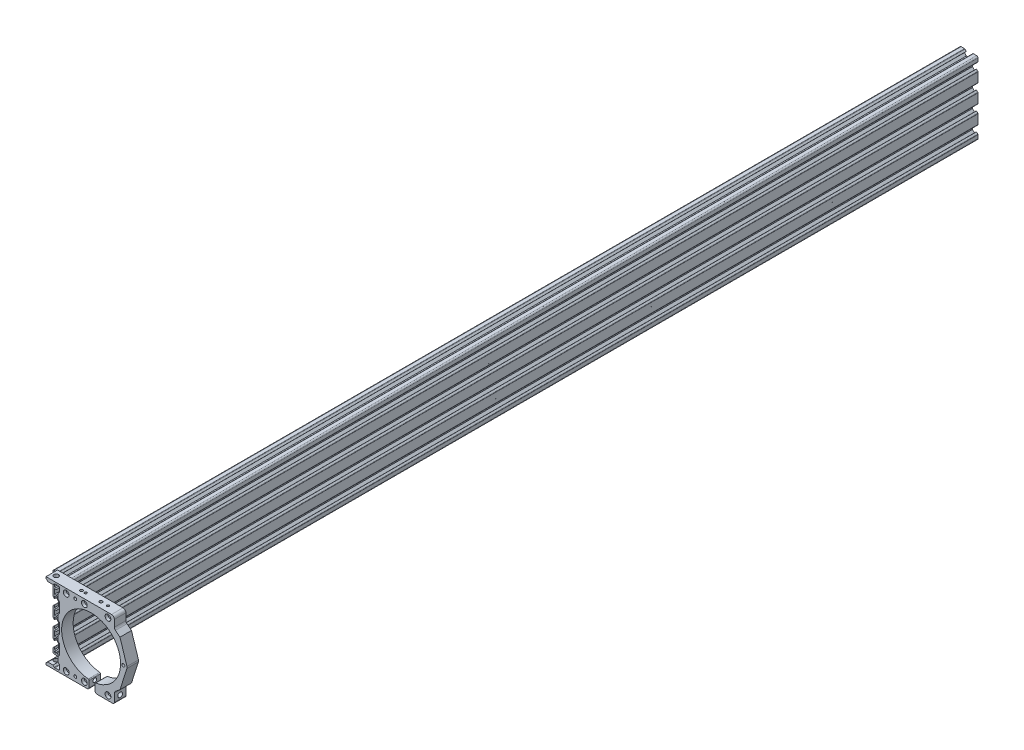
SolidWorks part; units mm, degrees
ref_plane "Front Plane" through (0, 0, 0) normal (0, 0, 1) x (1, 0, 0)
ref_plane "Top Plane" through (0, 0, 0) normal (0, 1, 0) x (1, 0, 0)
ref_plane "Right Plane" through (0, 0, 0) normal (1, 0, 0) x (0, 0, -1)
sketch "Sketch2" plane through (0, 0, 0) normal (0, 0, 1) x (1, 0, 0)
  line L0 (-8.2, 2.8875) -> (-8.2, 5.4975)
  line L3 (-4.9072, 9.9975) -> (-8.5, 9.9975)
  line L4 (-10, 4.9047) -> (-10, 8.4975)
  line L5 (-2.1, 0) -> (-3.8, 0) construction
  line L6 (0, 3.8) -> (0, 2.1) construction
  line L7 (-0.1, 3.9) -> (-2.8404, 3.9)
  line L8 (-3.9, 0.1) -> (-3.9, 2.8383)
  line L9 (-2.89, 8.1975) -> (-5.5, 8.1975)
  line L10 (-6.57, 8.1975) -> (-6.57, 7.6575)
  line L11 (-8.2, 6.5675) -> (-7.66, 6.5675)
  line L12 (-5.5, 8.1975) -> (-5.5, 6.5588)
  line L13 (-6.56, 5.4975) -> (-8.2, 5.4975)
  line L14 (-8.2, 8.1975) -> (-1.4852, 1.4847) construction
  line L15 (-6.56, 5.4975) -> (-3.9, 2.8383)
  line L16 (-5.5, 6.5588) -> (-2.8404, 3.9)
  line L17 (-7.66, 6.5675) -> (-6.57, 7.6575)
  line L18 (-8.7302, 7.6671) -> (-0.5302, -0.5304) construction
  line L19 (-7.6698, 8.7279) -> (0.5302, 0.5304) construction
  line L20 (-8.2, 8.1975) -> (0, 0) construction
  line L21 (-8.2, 6.5675) -> (-8.2, 8.1975)
  line L22 (-8.2, -0.0025) -> (-8.2, 8.1975) construction
  line L23 (-6.57, 8.1975) -> (-8.2, 8.1975)
  line L24 (0, 8.1975) -> (-8.2, 8.1975) construction
  line L25 (-10, -0.0025) -> (-10, 9.9975) construction
  line L26 (0, 9.9975) -> (-10, 9.9975) construction
  line L27 (-2.89, 8.3075) -> (-2.89, 8.1975)
  line L29 (-8.31, 2.8875) -> (-8.2, 2.8875)
  line L30 (-4.3486, 9.7661) -> (-2.89, 8.3075)
  line L31 (-8.31, 2.8875) -> (-9.7686, 4.3461)
  line L34 (-0.1, 3.9) -> (0, 3.8)
  line L35 (-3.9, 0.1) -> (-3.8, 0)
  line L36 (-10, -20) -> (0, -20) construction
  line L37 (0, 0) -> (0, -20) construction
  line L38 (0, -3.9) -> (-2.8404, -3.9)
  line L39 (-3.8, 0) -> (-3.9, -0.1)
  line L40 (-3.9, -0.1) -> (-3.9, -2.84)
  line L41 (-2.8404, -3.9) -> (-6.25, -7.3096)
  line L42 (-3.9, -2.84) -> (-6.56, -5.5)
  line L43 (-8.21, -2.89) -> (-8.21, -5.5)
  line L44 (-6.56, 5.4975) -> (-6.56, -5.5) construction
  line L45 (-6.56, -5.5) -> (-8.21, -5.5)
  line L46 (-6.25, -7.3096) -> (-6.25, -12.7) construction
  line L47 (-6.25, -7.3096) -> (-8.21, -7.3096)
  line L48 (-8.21, -2.89) -> (-8.31, -2.89)
  line L49 (-8.31, -2.89) -> (-9.7657, -4.3457)
  line L51 (-8.21, -7.3096) -> (-8.21, -12.7)
  line L52 (-0.1, -16.1) -> (-2.85, -16.1)
  line L53 (-3.9, -17.16) -> (-3.9, -19.9)
  line L54 (-6.25, -12.7) -> (-2.85, -16.1)
  line L58 (-3.9, -17.16) -> (-6.56, -14.5)
  line L60 (-8.21, -17.11) -> (-8.31, -17.11)
  line L61 (-10, -4.9114) -> (-10, -15.0886)
  line L62 (-9.7657, -15.6543) -> (-8.31, -17.11)
  line L63 (-0.1, -16.1) -> (0, -16.2)
  line L64 (-3.9, -19.9) -> (-3.8, -20)
  line L65 (-8.21, -14.5) -> (-6.56, -14.5)
  line L66 (-8.21, -12.7) -> (-6.25, -12.7)
  line L67 (-10, -30.01) -> (0, -30.01) construction
  line L68 (-8.21, -14.5) -> (-8.21, -17.11)
  line L69 (-3.9, -20.1) -> (-3.8, -20)
  line L71 (-10, -20) -> (0, -20) construction
  line L72 (-8.21, -30.01) -> (-8.21, -27.31)
  line L73 (-10, -30.01) -> (-10, -24.9101)
  line L74 (-8.21, -25.4987) -> (-8.21, -22.8887)
  line L76 (-8.21, -27.31) -> (-6.25, -27.31)
  line L77 (-8.21, -25.4987) -> (-6.56, -25.4987)
  line L85 (-0.1, -23.9) -> (0, -23.8)
  line L95 (-9.7657, -24.3444) -> (-8.31, -22.8887)
  line L96 (-8.21, -22.8887) -> (-8.31, -22.8887)
  line L97 (-3.9, -22.8387) -> (-6.56, -25.4987)
  line L98 (-6.25, -27.31) -> (-2.84, -23.9)
  line L99 (-3.9, -22.8387) -> (-3.9, -20.1)
  line L100 (-0.1, -23.9) -> (-2.84, -23.9)
  arc A1 (-10, 8.4975) -> (-8.5, 9.9975) centre (-8.5, 8.4975) cw
  arc A2 (-9.7686, 4.3461) -> (-10, 4.9047) centre (-9.21, 4.9047) cw
  arc A3 (-4.3486, 9.7661) -> (-4.9072, 9.9975) centre (-4.9072, 9.2075) ccw
  arc A5 (0, 2.1) -> (0, -2.1) centre (0, 0) ccw
  arc A6 (-9.7657, -15.6543) -> (-10, -15.0886) centre (-9.2, -15.0886) cw
  arc A7 (-9.7657, -4.3457) -> (-10, -4.9114) centre (-9.2, -4.9114) ccw
  arc A8 (0, -17.9) -> (0, -22.1) centre (0, -20) ccw
  arc A10 (-9.7657, -24.3444) -> (-10, -24.9101) centre (-9.2, -24.9101) ccw
  point P29 (-10, 9.9975)
  point P39 (-10, 4.5775)
  point P42 (-4.58, 9.9975)
  point P76 (-10, -15.42)
  point P79 (-10, -4.58)
  dimension "D15" = 1.5
  dimension "D22" = 0.79
  dimension "D30" = 2.1
  dimension "D31" = 2.1
  dimension "D51" = 0.8
  dimension "D52" = 2.61
  dimension "D64" = 1.65
  dimension "D53" = 0.8
  dimension "D55" = 3.9
  dimension "D4" = 1.8
  dimension "D5" = 3.43
  dimension "D6" = 3.43
  dimension "D7" = 0.54
  dimension "D8" = 0.54
  dimension "D9" = 1.07
  dimension "D10" = 1.07
  dimension "D11" = 3.9
  dimension "D12" = 3.9
  dimension "D16" = 7.11
  dimension "D17" = 0.11
  dimension "D18" = 1.69
  dimension "D19" = 0.11
  dimension "D20" = 7.11
  dimension "D21" = 1.69
  dimension "D23" = 10
  dimension "D24" = 0.1
  dimension "D25" = 45
  dimension "D26" = 0.1
  dimension "D27" = 45
  dimension "D28" = 1.64
  dimension "D29" = 20
  dimension "D32" = 3.9
  dimension "D33" = 45
  dimension "D34" = 2.74
  dimension "D35" = 45
  dimension "D36" = 1.96
  dimension "D37" = 2.61
  dimension "D38" = 90
  dimension "D39" = 2.61
  dimension "D40" = 3.9
  dimension "D41" = 3.9
  dimension "D42" = 135
  dimension "D44" = 45
  dimension "D45" = 1.8
  dimension "D46" = 0.1
  dimension "D47" = 0.1
  dimension "D48" = 45
  dimension "D49" = 0.1
  dimension "D50" = 45
  dimension "D43" = 5.5
  dimension "D54" = 3.9
  dimension "D56" = 45
  dimension "D57" = 2.7
  dimension "D59" = 45
  dimension "D60" = 0.1
  dimension "D61" = 0.1
  dimension "D62" = 45
  dimension "D63" = 2.84
  dimension "D65" = 1.96
  dimension "D66" = 45
  dimension "D67" = 1.5
  dimension "D13" = 0.75
  dimension "D14" = 0.75
sketch "Sketch3" plane through (0, 0, 0) normal (0, 0, 1) x (1, 0, 0)
  line L0 (-0.1, 3.9) -> (0, 3.8) construction
  line L1 (-0.1, 3.9) -> (-2.8404, 3.9) construction
  line L2 (-5.5, 6.5588) -> (-2.8404, 3.9) construction
  line L3 (-5.5, 8.1975) -> (-5.5, 6.5588) construction
  line L4 (-2.89, 8.1975) -> (-5.5, 8.1975) construction
  line L5 (-7.66, 6.5675) -> (-6.57, 7.6575)
  line L6 (-6.57, 7.6575) -> (-6.57, 8.1975)
  line L7 (-6.57, 8.1975) -> (-8.2, 8.1975)
  line L8 (-8.2, 8.1975) -> (-8.2, 6.5675)
  line L9 (-8.2, 6.5675) -> (-7.66, 6.5675)
  line L10 (-7.66, 6.5675) -> (-6.57, 7.6575)
  line L11 (-6.57, 7.6575) -> (-6.57, 8.1975)
  line L12 (-6.57, 8.1975) -> (-8.2, 8.1975)
  line L13 (-8.2, 8.1975) -> (-8.2, 6.5675)
  line L14 (-8.2, 6.5675) -> (-7.66, 6.5675)
  line L15 (-2.89, 8.3075) -> (-2.89, 8.1975) construction
  line L16 (-4.3486, 9.7661) -> (-2.89, 8.3075) construction
  line L17 (-4.9072, 9.9975) -> (-8.5, 9.9975) construction
  line L18 (-10, 4.9047) -> (-10, 8.4975) construction
  line L19 (-8.31, 2.8875) -> (-9.7686, 4.3461) construction
  line L20 (-8.31, 2.8875) -> (-8.2, 2.8875) construction
  line L21 (-8.2, 2.8875) -> (-8.2, 5.4975) construction
  line L22 (-6.56, 5.4975) -> (-8.2, 5.4975) construction
  line L23 (-6.56, 5.4975) -> (-3.9, 2.8383) construction
  line L24 (-3.9, 0.1) -> (-3.9, 2.8383) construction
  line L25 (-3.9, 0.1) -> (-3.8, 0) construction
  line L26 (-3.8, 0) -> (-3.9, -0.1) construction
  line L27 (-3.9, -0.1) -> (-3.9, -2.84) construction
  line L28 (-3.9, -2.84) -> (-6.56, -5.5) construction
  line L29 (-6.56, -5.5) -> (-8.21, -5.5) construction
  line L30 (-8.21, -2.89) -> (-8.21, -5.5) construction
  line L31 (-8.21, -2.89) -> (-8.31, -2.89) construction
  line L32 (-8.31, -2.89) -> (-9.7657, -4.3457) construction
  line L33 (-10, -4.9114) -> (-10, -15.0886) construction
  line L34 (-9.7657, -15.6543) -> (-8.31, -17.11) construction
  line L35 (-8.21, -17.11) -> (-8.31, -17.11) construction
  line L36 (-8.21, -14.5) -> (-8.21, -17.11) construction
  line L37 (-8.21, -14.5) -> (-6.56, -14.5) construction
  line L38 (-3.9, -17.16) -> (-6.56, -14.5) construction
  line L39 (-3.9, -17.16) -> (-3.9, -19.9) construction
  line L40 (-3.9, -19.9) -> (-3.8, -20) construction
  line L41 (-3.9, -20.1) -> (-3.8, -20) construction
  line L42 (-3.9, -22.8387) -> (-3.9, -20.1) construction
  line L43 (-3.9, -22.8387) -> (-6.56, -25.4987) construction
  line L44 (-8.21, -25.4987) -> (-6.56, -25.4987) construction
  line L45 (-8.21, -25.4987) -> (-8.21, -22.8887) construction
  line L46 (-8.21, -22.8887) -> (-8.31, -22.8887) construction
  line L47 (-9.7657, -24.3444) -> (-8.31, -22.8887) construction
  line L48 (-10, -30.01) -> (-10, -24.9101) construction
  line L49 (0, -3.9) -> (-2.8404, -3.9) construction
  line L50 (-2.8404, -3.9) -> (-6.25, -7.3096) construction
  line L51 (-6.25, -7.3096) -> (-8.21, -7.3096) construction
  line L52 (-8.21, -7.3096) -> (-8.21, -12.7) construction
  line L53 (-8.21, -12.7) -> (-6.25, -12.7) construction
  line L54 (-6.25, -12.7) -> (-2.85, -16.1) construction
  line L55 (-0.1, -16.1) -> (-2.85, -16.1) construction
  line L56 (-0.1, -16.1) -> (0, -16.2) construction
  line L57 (-0.1, -23.9) -> (0, -23.8) construction
  line L58 (-0.1, -23.9) -> (-2.84, -23.9) construction
  line L59 (-6.25, -27.31) -> (-2.84, -23.9) construction
  line L60 (-8.21, -27.31) -> (-6.25, -27.31) construction
  line L61 (-8.21, -30.01) -> (-8.21, -27.31) construction
  line L62 (-0.1, 3.9) -> (0, 3.8)
  line L63 (-0.1, 3.9) -> (-2.8404, 3.9)
  line L64 (-5.5, 6.5588) -> (-2.8404, 3.9)
  line L65 (-5.5, 8.1975) -> (-5.5, 6.5588)
  line L66 (-2.89, 8.1975) -> (-5.5, 8.1975)
  line L67 (-2.89, 8.3075) -> (-2.89, 8.1975)
  line L68 (-4.3486, 9.7661) -> (-2.89, 8.3075)
  line L69 (-4.9072, 9.9975) -> (-8.5, 9.9975)
  line L70 (-10, 4.9047) -> (-10, 8.4975)
  line L71 (-8.31, 2.8875) -> (-9.7686, 4.3461)
  line L72 (-8.31, 2.8875) -> (-8.2, 2.8875)
  line L73 (-8.2, 2.8875) -> (-8.2, 5.4975)
  line L74 (-6.56, 5.4975) -> (-8.2, 5.4975)
  line L75 (-6.56, 5.4975) -> (-3.9, 2.8383)
  line L76 (-3.9, 0.1) -> (-3.9, 2.8383)
  line L77 (-3.9, 0.1) -> (-3.8, 0)
  line L78 (-3.8, 0) -> (-3.9, -0.1)
  line L79 (-3.9, -0.1) -> (-3.9, -2.84)
  line L80 (-3.9, -2.84) -> (-6.56, -5.5)
  line L81 (-6.56, -5.5) -> (-8.21, -5.5)
  line L82 (-8.21, -2.89) -> (-8.21, -5.5)
  line L83 (-8.21, -2.89) -> (-8.31, -2.89)
  line L84 (-8.31, -2.89) -> (-9.7657, -4.3457)
  line L85 (-10, -4.9114) -> (-10, -15.0886)
  line L86 (-9.7657, -15.6543) -> (-8.31, -17.11)
  line L87 (-8.21, -17.11) -> (-8.31, -17.11)
  line L88 (-8.21, -14.5) -> (-8.21, -17.11)
  line L89 (-8.21, -14.5) -> (-6.56, -14.5)
  line L90 (-3.9, -17.16) -> (-6.56, -14.5)
  line L91 (-3.9, -17.16) -> (-3.9, -19.9)
  line L92 (-3.9, -19.9) -> (-3.8, -20)
  line L93 (-3.9, -20.1) -> (-3.8, -20)
  line L94 (-3.9, -22.8387) -> (-3.9, -20.1)
  line L95 (-3.9, -22.8387) -> (-6.56, -25.4987)
  line L96 (-8.21, -25.4987) -> (-6.56, -25.4987)
  line L97 (-8.21, -25.4987) -> (-8.21, -22.8887)
  line L98 (-8.21, -22.8887) -> (-8.31, -22.8887)
  line L99 (-9.7657, -24.3444) -> (-8.31, -22.8887)
  line L100 (-10, -35.1099) -> (-10, -24.9101)
  line L101 (2.8404, -3.9) -> (-2.8404, -3.9)
  line L102 (-2.8404, -3.9) -> (-6.25, -7.3096)
  line L103 (-6.25, -7.3096) -> (-8.21, -7.3096)
  line L104 (-8.21, -7.3096) -> (-8.21, -12.7)
  line L105 (-8.21, -12.7) -> (-6.25, -12.7)
  line L106 (-6.25, -12.7) -> (-2.85, -16.1)
  line L107 (-0.1, -16.1) -> (-2.85, -16.1)
  line L108 (-0.1, -16.1) -> (0, -16.2)
  line L109 (-0.1, -23.9) -> (0, -23.8)
  line L110 (-0.1, -23.9) -> (-2.84, -23.9)
  line L111 (-6.25, -27.31) -> (-2.84, -23.9)
  line L112 (-8.21, -27.31) -> (-6.25, -27.31)
  line L113 (-8.21, -32.71) -> (-8.21, -27.31)
  line L114 (0, 0) -> (0, -20) construction
  line L115 (-10, -30.01) -> (0, -30.01) construction
  line L116 (0, 0) -> (0, -20) construction
  line L117 (-10, -30.01) -> (10, -30.01) construction
  line L118 (8.21, -32.71) -> (8.21, -27.31)
  line L119 (8.21, -27.31) -> (6.25, -27.31)
  line L120 (6.25, -27.31) -> (2.84, -23.9)
  line L121 (0.1, -23.9) -> (2.84, -23.9)
  line L122 (0.1, -23.9) -> (0, -23.8)
  line L123 (0.1, -16.1) -> (0, -16.2)
  line L124 (0.1, -16.1) -> (2.85, -16.1)
  line L125 (6.25, -12.7) -> (2.85, -16.1)
  line L126 (8.21, -12.7) -> (6.25, -12.7)
  line L127 (8.21, -7.3096) -> (8.21, -12.7)
  line L128 (6.25, -7.3096) -> (8.21, -7.3096)
  line L129 (2.8404, -3.9) -> (6.25, -7.3096)
  line L130 (10, -35.1099) -> (10, -24.9101)
  line L131 (9.7657, -24.3444) -> (8.31, -22.8887)
  line L132 (8.21, -22.8887) -> (8.31, -22.8887)
  line L133 (8.21, -25.4987) -> (8.21, -22.8887)
  line L134 (8.21, -25.4987) -> (6.56, -25.4987)
  line L135 (3.9, -22.8387) -> (6.56, -25.4987)
  line L136 (3.9, -22.8387) -> (3.9, -20.1)
  line L137 (3.9, -20.1) -> (3.8, -20)
  line L138 (3.9, -19.9) -> (3.8, -20)
  line L139 (3.9, -17.16) -> (3.9, -19.9)
  line L140 (3.9, -17.16) -> (6.56, -14.5)
  line L141 (8.21, -14.5) -> (6.56, -14.5)
  line L142 (8.21, -14.5) -> (8.21, -17.11)
  line L143 (8.21, -17.11) -> (8.31, -17.11)
  line L144 (9.7657, -15.6543) -> (8.31, -17.11)
  line L145 (10, -4.9114) -> (10, -15.0886)
  line L146 (8.31, -2.89) -> (9.7657, -4.3457)
  line L147 (8.21, -2.89) -> (8.31, -2.89)
  line L148 (8.21, -2.89) -> (8.21, -5.5)
  line L149 (6.56, -5.5) -> (8.21, -5.5)
  line L150 (3.9, -2.84) -> (6.56, -5.5)
  line L151 (3.9, -0.1) -> (3.9, -2.84)
  line L152 (3.8, 0) -> (3.9, -0.1)
  line L153 (3.9, 0.1) -> (3.8, 0)
  line L154 (3.9, 0.1) -> (3.9, 2.8383)
  line L155 (6.56, 5.4975) -> (3.9, 2.8383)
  line L156 (6.56, 5.4975) -> (8.2, 5.4975)
  line L157 (8.2, 2.8875) -> (8.2, 5.4975)
  line L158 (8.31, 2.8875) -> (8.2, 2.8875)
  line L159 (8.31, 2.8875) -> (9.7686, 4.3461)
  line L160 (10, 4.9047) -> (10, 8.4975)
  line L161 (4.9072, 9.9975) -> (8.5, 9.9975)
  line L162 (4.3486, 9.7661) -> (2.89, 8.3075)
  line L163 (2.89, 8.3075) -> (2.89, 8.1975)
  line L164 (2.89, 8.1975) -> (5.5, 8.1975)
  line L165 (5.5, 8.1975) -> (5.5, 6.5588)
  line L166 (5.5, 6.5588) -> (2.8404, 3.9)
  line L167 (0.1, 3.9) -> (2.8404, 3.9)
  line L168 (0.1, 3.9) -> (0, 3.8)
  line L169 (8.2, 6.5675) -> (7.66, 6.5675)
  line L170 (8.2, 8.1975) -> (8.2, 6.5675)
  line L171 (6.57, 8.1975) -> (8.2, 8.1975)
  line L172 (6.57, 7.6575) -> (6.57, 8.1975)
  line L173 (7.66, 6.5675) -> (6.57, 7.6575)
  line L174 (0, -60.02) -> (0, -40.02) construction
  line L175 (7.66, -66.5875) -> (6.57, -67.6775)
  line L176 (6.57, -67.6775) -> (6.57, -68.2175)
  line L177 (6.57, -68.2175) -> (8.2, -68.2175)
  line L178 (8.2, -68.2175) -> (8.2, -66.5875)
  line L179 (8.2, -66.5875) -> (7.66, -66.5875)
  line L180 (0.1, -63.92) -> (0, -63.82)
  line L181 (0.1, -63.92) -> (2.8404, -63.92)
  line L182 (5.5, -66.5788) -> (2.8404, -63.92)
  line L183 (5.5, -68.2175) -> (5.5, -66.5788)
  line L184 (2.89, -68.2175) -> (5.5, -68.2175)
  line L185 (2.89, -68.3275) -> (2.89, -68.2175)
  line L186 (4.3486, -69.7861) -> (2.89, -68.3275)
  line L187 (4.9072, -70.0175) -> (8.5, -70.0175)
  line L188 (10, -64.9247) -> (10, -68.5175)
  line L189 (8.31, -62.9075) -> (9.7686, -64.3661)
  line L190 (8.31, -62.9075) -> (8.2, -62.9075)
  line L191 (8.2, -62.9075) -> (8.2, -65.5175)
  line L192 (6.56, -65.5175) -> (8.2, -65.5175)
  line L193 (6.56, -65.5175) -> (3.9, -62.8583)
  line L194 (3.9, -60.12) -> (3.9, -62.8583)
  line L195 (3.9, -60.12) -> (3.8, -60.02)
  line L196 (3.8, -60.02) -> (3.9, -59.92)
  line L197 (3.9, -59.92) -> (3.9, -57.18)
  line L198 (3.9, -57.18) -> (6.56, -54.52)
  line L199 (6.56, -54.52) -> (8.21, -54.52)
  line L200 (8.21, -57.13) -> (8.21, -54.52)
  line L201 (8.21, -57.13) -> (8.31, -57.13)
  line L202 (8.31, -57.13) -> (9.7657, -55.6743)
  line L203 (10, -55.1086) -> (10, -44.9314)
  line L204 (9.7657, -44.3657) -> (8.31, -42.91)
  line L205 (8.21, -42.91) -> (8.31, -42.91)
  line L206 (8.21, -45.52) -> (8.21, -42.91)
  line L207 (8.21, -45.52) -> (6.56, -45.52)
  line L208 (3.9, -42.86) -> (6.56, -45.52)
  line L209 (3.9, -42.86) -> (3.9, -40.12)
  line L210 (3.9, -40.12) -> (3.8, -40.02)
  line L211 (3.9, -39.92) -> (3.8, -40.02)
  line L212 (3.9, -37.1813) -> (3.9, -39.92)
  line L213 (3.9, -37.1813) -> (6.56, -34.5213)
  line L214 (8.21, -34.5213) -> (6.56, -34.5213)
  line L215 (8.21, -34.5213) -> (8.21, -37.1313)
  line L216 (8.21, -37.1313) -> (8.31, -37.1313)
  line L217 (9.7657, -35.6756) -> (8.31, -37.1313)
  line L218 (2.8404, -56.12) -> (6.25, -52.7104)
  line L219 (6.25, -52.7104) -> (8.21, -52.7104)
  line L220 (8.21, -52.7104) -> (8.21, -47.32)
  line L221 (8.21, -47.32) -> (6.25, -47.32)
  line L222 (6.25, -47.32) -> (2.85, -43.92)
  line L223 (0.1, -43.92) -> (2.85, -43.92)
  line L224 (0.1, -43.92) -> (0, -43.82)
  line L225 (0.1, -36.12) -> (0, -36.22)
  line L226 (0.1, -36.12) -> (2.84, -36.12)
  line L227 (6.25, -32.71) -> (2.84, -36.12)
  line L228 (8.21, -32.71) -> (6.25, -32.71)
  line L229 (-8.21, -32.71) -> (-6.25, -32.71)
  line L230 (-6.25, -32.71) -> (-2.84, -36.12)
  line L231 (-0.1, -36.12) -> (-2.84, -36.12)
  line L232 (-0.1, -36.12) -> (0, -36.22)
  line L233 (-0.1, -43.92) -> (0, -43.82)
  line L234 (-0.1, -43.92) -> (-2.85, -43.92)
  line L235 (-6.25, -47.32) -> (-2.85, -43.92)
  line L236 (-8.21, -47.32) -> (-6.25, -47.32)
  line L237 (-8.21, -52.7104) -> (-8.21, -47.32)
  line L238 (-6.25, -52.7104) -> (-8.21, -52.7104)
  line L239 (-2.8404, -56.12) -> (-6.25, -52.7104)
  line L240 (2.8404, -56.12) -> (-2.8404, -56.12)
  line L241 (-9.7657, -35.6756) -> (-8.31, -37.1313)
  line L242 (-8.21, -37.1313) -> (-8.31, -37.1313)
  line L243 (-8.21, -34.5213) -> (-8.21, -37.1313)
  line L244 (-8.21, -34.5213) -> (-6.56, -34.5213)
  line L245 (-3.9, -37.1813) -> (-6.56, -34.5213)
  line L246 (-3.9, -37.1813) -> (-3.9, -39.92)
  line L247 (-3.9, -39.92) -> (-3.8, -40.02)
  line L248 (-3.9, -40.12) -> (-3.8, -40.02)
  line L249 (-3.9, -42.86) -> (-3.9, -40.12)
  line L250 (-3.9, -42.86) -> (-6.56, -45.52)
  line L251 (-8.21, -45.52) -> (-6.56, -45.52)
  line L252 (-8.21, -45.52) -> (-8.21, -42.91)
  line L253 (-8.21, -42.91) -> (-8.31, -42.91)
  line L254 (-9.7657, -44.3657) -> (-8.31, -42.91)
  line L255 (-10, -55.1086) -> (-10, -44.9314)
  line L256 (-8.31, -57.13) -> (-9.7657, -55.6743)
  line L257 (-8.21, -57.13) -> (-8.31, -57.13)
  line L258 (-8.21, -57.13) -> (-8.21, -54.52)
  line L259 (-6.56, -54.52) -> (-8.21, -54.52)
  line L260 (-3.9, -57.18) -> (-6.56, -54.52)
  line L261 (-3.9, -59.92) -> (-3.9, -57.18)
  line L262 (-3.8, -60.02) -> (-3.9, -59.92)
  line L263 (-3.9, -60.12) -> (-3.8, -60.02)
  line L264 (-3.9, -60.12) -> (-3.9, -62.8583)
  line L265 (-6.56, -65.5175) -> (-3.9, -62.8583)
  line L266 (-6.56, -65.5175) -> (-8.2, -65.5175)
  line L267 (-8.2, -62.9075) -> (-8.2, -65.5175)
  line L268 (-8.31, -62.9075) -> (-8.2, -62.9075)
  line L269 (-8.31, -62.9075) -> (-9.7686, -64.3661)
  line L270 (-10, -64.9247) -> (-10, -68.5175)
  line L271 (-4.9072, -70.0175) -> (-8.5, -70.0175)
  line L272 (-4.3486, -69.7861) -> (-2.89, -68.3275)
  line L273 (-2.89, -68.3275) -> (-2.89, -68.2175)
  line L274 (-2.89, -68.2175) -> (-5.5, -68.2175)
  line L275 (-5.5, -68.2175) -> (-5.5, -66.5788)
  line L276 (-5.5, -66.5788) -> (-2.8404, -63.92)
  line L277 (-0.1, -63.92) -> (-2.8404, -63.92)
  line L278 (-0.1, -63.92) -> (0, -63.82)
  line L279 (-8.2, -66.5875) -> (-7.66, -66.5875)
  line L280 (-8.2, -68.2175) -> (-8.2, -66.5875)
  line L281 (-6.57, -68.2175) -> (-8.2, -68.2175)
  line L282 (-6.57, -67.6775) -> (-6.57, -68.2175)
  line L283 (-7.66, -66.5875) -> (-6.57, -67.6775)
  arc A0 (0, 2.1) -> (0, -2.1) centre (0, 0) ccw construction
  arc A1 (0, -17.9) -> (0, -22.1) centre (0, -20) ccw construction
  arc A2 (-4.3486, 9.7661) -> (-4.9072, 9.9975) centre (-4.9072, 9.2075) ccw construction
  arc A3 (-8.5, 9.9975) -> (-10, 8.4975) centre (-8.5, 8.4975) ccw construction
  arc A4 (-10, 4.9047) -> (-9.7686, 4.3461) centre (-9.21, 4.9047) ccw construction
  arc A5 (-9.7657, -4.3457) -> (-10, -4.9114) centre (-9.2, -4.9114) ccw construction
  arc A6 (-10, -15.0886) -> (-9.7657, -15.6543) centre (-9.2, -15.0886) ccw construction
  arc A7 (-9.7657, -24.3444) -> (-10, -24.9101) centre (-9.2, -24.9101) ccw construction
  circle A8 centre (0, 0) radius 2.1
  circle A9 centre (0, -20) radius 2.1
  arc A10 (-4.3486, 9.7661) -> (-4.9072, 9.9975) centre (-4.9072, 9.2075) ccw
  arc A11 (-8.5, 9.9975) -> (-10, 8.4975) centre (-8.5, 8.4975) ccw
  arc A12 (-10, 4.9047) -> (-9.7686, 4.3461) centre (-9.21, 4.9047) ccw
  arc A13 (-9.7657, -4.3457) -> (-10, -4.9114) centre (-9.2, -4.9114) ccw
  arc A14 (-10, -15.0886) -> (-9.7657, -15.6543) centre (-9.2, -15.0886) ccw
  arc A15 (-9.7657, -24.3444) -> (-10, -24.9101) centre (-9.2, -24.9101) ccw
  arc A16 (9.7657, -24.3444) -> (10, -24.9101) centre (9.2, -24.9101) cw
  arc A17 (10, -15.0886) -> (9.7657, -15.6543) centre (9.2, -15.0886) cw
  arc A18 (9.7657, -4.3457) -> (10, -4.9114) centre (9.2, -4.9114) cw
  arc A19 (10, 4.9047) -> (9.7686, 4.3461) centre (9.21, 4.9047) cw
  arc A20 (8.5, 9.9975) -> (10, 8.4975) centre (8.5, 8.4975) cw
  arc A21 (4.3486, 9.7661) -> (4.9072, 9.9975) centre (4.9072, 9.2075) cw
  arc A22 (4.3486, -69.7861) -> (4.9072, -70.0175) centre (4.9072, -69.2275) ccw
  arc A23 (8.5, -70.0175) -> (10, -68.5175) centre (8.5, -68.5175) ccw
  arc A24 (10, -64.9247) -> (9.7686, -64.3661) centre (9.21, -64.9247) ccw
  arc A25 (9.7657, -55.6743) -> (10, -55.1086) centre (9.2, -55.1086) ccw
  arc A26 (10, -44.9314) -> (9.7657, -44.3657) centre (9.2, -44.9314) ccw
  arc A27 (9.7657, -35.6756) -> (10, -35.1099) centre (9.2, -35.1099) ccw
  arc A28 (-9.7657, -35.6756) -> (-10, -35.1099) centre (-9.2, -35.1099) cw
  arc A29 (-10, -44.9314) -> (-9.7657, -44.3657) centre (-9.2, -44.9314) cw
  arc A30 (-9.7657, -55.6743) -> (-10, -55.1086) centre (-9.2, -55.1086) cw
  arc A31 (-10, -64.9247) -> (-9.7686, -64.3661) centre (-9.21, -64.9247) cw
  arc A32 (-8.5, -70.0175) -> (-10, -68.5175) centre (-8.5, -68.5175) cw
  arc A33 (-4.3486, -69.7861) -> (-4.9072, -70.0175) centre (-4.9072, -69.2275) cw
  circle A34 centre (0, -40.02) radius 2.1
  circle A35 centre (0, -60.02) radius 2.1
  point P240 (8.21, -30.01)
  point P288 (-0.1, 9.9975)
  point P289 (0, -70.0175)
  point P290 (-10, -60.02)
  point P291 (10, -60.02)
  point P292 (10, -40.02)
  point P293 (-10, -40.02)
  point P294 (-10, -20)
  point P295 (10, -20)
  point P296 (10, 0)
  point P297 (-10, 0)
  point P298 (-45.6583, 8.4975)
  dimension "D1" = 0
extrude "Boss-Extrude1" add sketch "Sketch3" against normal blind 1000
sketch "Sketch7" plane through (0, 0, 0) normal (0, 0, 1) x (1, 0, 0)
  line L0 (-10, -24.9101) -> (-10, -35.1099) construction
  line L1 (-8.2, -68.2175) -> (-6.57, -68.2175) construction
  line L2 (10.1, 12.0975) -> (67.3634, 12.0975)
  line L3 (70.4884, -70.1175) -> (70.4884, -61.5188)
  line L4 (8.3807, 2.8168) -> (9.8393, 4.2754)
  line L5 (10.1, 4.9047) -> (10.1, 8.4975)
  line L6 (8.3807, 2.8168) -> (9.8393, 4.2754)
  line L7 (10.1, 4.9047) -> (10.1, 8.4975)
  line L8 (49.1638, -63.0778) -> (49.1638, -70.1175)
  line L9 (70.4884, 1.4988) -> (70.4884, 8.9725)
  line L10 (51.1638, -72.1175) -> (68.4884, -72.1175)
  line L11 (42.5638, -63.3533) -> (42.5638, -70.1175)
  line L12 (8.3807, -17.1807) -> (9.8364, -15.725)
  line L13 (10.1, -15.0886) -> (10.1, -4.9114)
  line L14 (9.8364, -4.275) -> (8.3807, -2.8193)
  line L15 (8.3807, -17.1807) -> (9.8364, -15.725)
  line L16 (10.1, -15.0886) -> (10.1, -4.9114)
  line L17 (9.8364, -4.275) -> (8.3807, -2.8193)
  line L18 (40.5638, -72.1175) -> (10.1, -72.1175)
  line L34 (8.3807, -37.202) -> (9.8364, -35.7463)
  line L35 (10.1, -35.1099) -> (10.1, -24.9101)
  line L36 (9.8364, -24.2737) -> (8.3807, -22.818)
  line L37 (8.3807, -37.202) -> (9.8364, -35.7463)
  line L38 (10.1, -35.1099) -> (10.1, -24.9101)
  line L39 (9.8364, -24.2737) -> (8.3807, -22.818)
  line L43 (8.3807, -57.2007) -> (9.8364, -55.745)
  line L44 (10.1, -55.1086) -> (10.1, -44.9314)
  line L45 (9.8364, -44.295) -> (8.3807, -42.8393)
  line L46 (8.3807, -57.2007) -> (9.8364, -55.745)
  line L47 (10.1, -55.1086) -> (10.1, -44.9314)
  line L48 (9.8364, -44.295) -> (8.3807, -42.8393)
  line L54 (10.1, -68.5175) -> (10.1, -64.9247)
  line L55 (9.8393, -64.2954) -> (8.3807, -62.8368)
  line L56 (10.1, -68.5175) -> (10.1, -64.9247)
  line L57 (9.8393, -64.2954) -> (8.3807, -62.8368)
  line L62 (4.2779, 9.8368) -> (2.8193, 8.3782)
  line L63 (8.5, 10.0975) -> (4.9072, 10.0975)
  line L64 (4.2779, 9.8368) -> (2.8193, 8.3782)
  line L65 (8.5, 10.0975) -> (4.9072, 10.0975)
  line L70 (2.8193, -68.3982) -> (4.2779, -69.8568)
  line L71 (4.9072, -70.1175) -> (8.5, -70.1175)
  line L72 (2.8193, -68.3982) -> (4.2779, -69.8568)
  line L73 (4.9072, -70.1175) -> (8.5, -70.1175)
  line L74 (-4.2779, -69.8568) -> (-2.8193, -68.3982)
  line L75 (-4.2779, -69.8568) -> (-2.8193, -68.3982)
  line L76 (-2.8193, 8.3782) -> (2.8193, 8.3782)
  line L77 (-2.8193, 8.3782) -> (-4.2779, 9.8368)
  line L78 (-2.8193, 8.3782) -> (-4.2779, 9.8368)
  line L79 (8.3807, 2.8168) -> (8.3807, -2.8193)
  line L80 (8.3807, -17.1807) -> (8.3807, -22.818)
  line L81 (8.3807, -22.818) -> (8.3807, -17.1807)
  line L82 (8.3807, -37.202) -> (8.3807, -42.8393)
  line L83 (8.3807, -57.2007) -> (8.3807, -62.8368)
  line L84 (2.8193, -68.3982) -> (-2.8193, -68.3982)
  line L85 (-4.9072, 10.0975) -> (-4.9072, 12.0975)
  line L86 (-4.9072, 12.0975) -> (10.1, 12.0975)
  line L87 (-4.9072, -70.1175) -> (-4.9072, -72.1175)
  line L88 (-4.9072, -72.1175) -> (10.1, -72.1175)
  line L89 (8.21, -32.71) -> (8.21, -27.31) construction
  line L90 (8.21, -30.01) -> (-8.21, -30.01) construction
  line L91 (-8.21, -27.31) -> (-8.21, -32.71) construction
  line L92 (-8.21, -30.01) -> (44.8, -30.01) construction
  line L97 (71.6683, -0.947) -> (76.653, -4.9114)
  line L98 (76.653, -4.9114) -> (84.3348, -29.0628)
  line L99 (76.653, -55.1086) -> (84.3348, -30.9572)
  line L100 (71.6683, -59.073) -> (76.653, -55.1086)
  arc A0 (51.1638, -72.1175) -> (49.1638, -70.1175) centre (51.1638, -70.1175) cw
  arc A1 (40.5638, -72.1175) -> (42.5638, -70.1175) centre (40.5638, -70.1175) ccw
  arc A2 (70.4884, 1.4988) -> (71.6683, -0.947) centre (73.6134, 1.4988) ccw
  arc A3 (84.3348, -29.0628) -> (84.3348, -30.9572) centre (81.3568, -30.01) cw
  arc A4 (9.8393, 4.2754) -> (10.1, 4.9047) centre (9.21, 4.9047) ccw
  arc A5 (10.1, 8.4975) -> (8.5, 10.0975) centre (8.5, 8.4975) ccw
  arc A6 (9.8393, 4.2754) -> (10.1, 4.9047) centre (9.21, 4.9047) ccw
  arc A7 (10.1, 8.4975) -> (8.5, 10.0975) centre (8.5, 8.4975) ccw
  arc A8 (70.4884, -61.5188) -> (71.6683, -59.073) centre (73.6134, -61.5188) cw
  arc A9 (68.4884, -72.1175) -> (70.4884, -70.1175) centre (68.4884, -70.1175) ccw
  arc A10 (9.8364, -15.725) -> (10.1, -15.0886) centre (9.2, -15.0886) ccw
  arc A11 (10.1, -4.9114) -> (9.8364, -4.275) centre (9.2, -4.9114) ccw
  arc A12 (9.8364, -15.725) -> (10.1, -15.0886) centre (9.2, -15.0886) ccw
  arc A13 (10.1, -4.9114) -> (9.8364, -4.275) centre (9.2, -4.9114) ccw
  arc A14 (67.3634, 12.0975) -> (70.4884, 8.9725) centre (67.3634, 8.9725) cw
  arc A15 (49.1638, -63.0778) -> (50.0037, -62.0907) centre (50.1638, -63.0778) cw
  arc A16 (41.6604, -62.358) -> (42.5638, -63.3533) centre (41.5638, -63.3533) cw
  arc A24 (9.8364, -35.7463) -> (10.1, -35.1099) centre (9.2, -35.1099) ccw
  arc A25 (10.1, -24.9101) -> (9.8364, -24.2737) centre (9.2, -24.9101) ccw
  arc A26 (9.8364, -35.7463) -> (10.1, -35.1099) centre (9.2, -35.1099) ccw
  arc A27 (10.1, -24.9101) -> (9.8364, -24.2737) centre (9.2, -24.9101) ccw
  arc A30 (9.8364, -55.745) -> (10.1, -55.1086) centre (9.2, -55.1086) ccw
  arc A31 (10.1, -44.9314) -> (9.8364, -44.295) centre (9.2, -44.9314) ccw
  arc A32 (9.8364, -55.745) -> (10.1, -55.1086) centre (9.2, -55.1086) ccw
  arc A33 (10.1, -44.9314) -> (9.8364, -44.295) centre (9.2, -44.9314) ccw
  arc A38 (8.5, -70.1175) -> (10.1, -68.5175) centre (8.5, -68.5175) ccw
  arc A39 (10.1, -64.9247) -> (9.8393, -64.2954) centre (9.21, -64.9247) ccw
  arc A40 (8.5, -70.1175) -> (10.1, -68.5175) centre (8.5, -68.5175) ccw
  arc A41 (10.1, -64.9247) -> (9.8393, -64.2954) centre (9.21, -64.9247) ccw
  arc A43 (4.9072, 10.0975) -> (4.2779, 9.8368) centre (4.9072, 9.2075) ccw
  arc A44 (4.9072, 10.0975) -> (4.2779, 9.8368) centre (4.9072, 9.2075) ccw
  arc A47 (4.2779, -69.8568) -> (4.9072, -70.1175) centre (4.9072, -69.2275) ccw
  arc A48 (4.2779, -69.8568) -> (4.9072, -70.1175) centre (4.9072, -69.2275) ccw
  arc A50 (-4.9072, -70.1175) -> (-4.2779, -69.8568) centre (-4.9072, -69.2275) ccw
  arc A51 (-4.9072, -70.1175) -> (-4.2779, -69.8568) centre (-4.9072, -69.2275) ccw
  arc A52 (50.0037, -62.0907) -> (41.6604, -62.358) centre (44.8, -30.01) ccw
  arc A53 (-4.2779, 9.8368) -> (-4.9072, 10.0975) centre (-4.9072, 9.2075) ccw
  arc A54 (-4.2779, 9.8368) -> (-4.9072, 10.0975) centre (-4.9072, 9.2075) ccw
  point P67 (70.4884, -74.1217)
  point P80 (49.1638, -73.747)
  point P81 (0, 0)
  point P84 (42.5638, -73.9337)
  point P88 (70.4884, -0.0087)
  point P91 (84.6361, -30.01)
  point P94 (70.4884, -60.0113)
  point P99 (0, 0)
  point P100 (0, 0)
  point P101 (0, 0)
  point P102 (0, 0)
  point P103 (0, 0)
  point P104 (0, 0)
  point P105 (0, 0)
  point P106 (70.4884, -72.1175)
  point P108 (42.5638, -72.1175)
  point P110 (49.1638, -72.1175)
  point P116 (42.5638, -62.433)
  point P117 (0, 0)
  point P118 (0, 0)
  point P119 (0, 0)
  point P120 (0, 0)
  point P121 (0, 0)
  dimension "D10" = 3.43
  dimension "D13" = 2
  dimension "D14" = 6.6
  dimension "D15" = 2
  dimension "D16" = 2
  dimension "D17" = 1
  dimension "D11" = 43.3075
  dimension "D12" = 80.315
  dimension "D1" = 0.1
  dimension "D2" = 0.1
  dimension "D3" = 0.1
  dimension "D4" = 0.1
  dimension "D5" = 0.1
  dimension "D6" = 0.1
  dimension "D7" = 0.1
  dimension "D8" = 0.1
  dimension "D9" = 0.1
extrude "Boss-Extrude2" add sketch "Sketch7" along normal blind 12.7 separate body
sketch "Sketch8" plane through (0, 0, 0) normal (0, 0, -1) x (-1, 0, 0)
  line L0 (-44.8, -30.01) -> (-44.8, 12.0975) construction
  line L1 (4.9072, 12.0975) -> (-67.3634, 12.0975) construction
sketch "Sketch10" plane through (70.4884, 0, 0) normal (1, 0, 0) x (0, 0, -1)
  circle A0 centre (-6.35, -66.1862) radius 2.6
extrude "Cut-Extrude1" cut sketch "Sketch10" against normal up to vertex (21.3246 mm away)
sketch "Sketch11" plane through (0, 12.0975, 0) normal (0, 1, 0) x (1, 0, 0)
  line L0 (44.7995, 0) -> (44.7995, -12.7) construction
  line L1 (44.7995, -6.35) -> (57.0995, -6.35) construction
  line L2 (44.7995, -6.35) -> (32.4995, -6.35) construction
  line L3 (44.7995, -6.35) -> (27.9425, -6.35) construction
  line L4 (27.9425, -6.35) -> (49.3425, -6.35) construction
  circle A0 centre (32.4995, -6.35) radius 1.25
  circle A1 centre (57.0995, -6.35) radius 1.25
  circle A2 centre (27.9425, -6.35) radius 1.65
  circle A3 centre (49.3425, -6.35) radius 1.65
extrude "Cut-Extrude2" cut sketch "Sketch11" against normal blind 10
sketch "Sketch12" plane through (0, 0, 0) normal (0, 0, -1) x (-1, 0, 0)
  line L0 (-37.4013, -67.1175) -> (-63.4013, -67.1175) construction
  line L1 (-63.4013, -67.1175) -> (-63.4013, -72.1175) construction
  line L2 (-51.1638, -72.1175) -> (-68.4884, -72.1175) construction
  line L3 (-63.4013, 12.0975) -> (-63.4013, 7.0975) construction
  line L4 (4.9072, 12.0975) -> (-67.3634, 12.0975) construction
  line L5 (-63.4013, 7.0975) -> (-37.4013, 7.0975) construction
  line L6 (-17.4013, -67.1175) -> (-37.4013, -67.1175) construction
  line L7 (-37.4013, 7.0975) -> (-17.4013, 7.0975) construction
  line L8 (-17.4013, -67.1175) -> (-63.4013, 7.0975) construction
  line L9 (-63.4013, 7.0975) -> (-63.4013, -67.1175) construction
  line L10 (-63.4013, -67.1175) -> (-17.4013, 7.0975) construction
  line L11 (-40.4013, -30.01) -> (-44.8, -30.01) construction
  line L12 (-40.4013, -30.01) -> (-80.4013, -30.01) construction
  circle A0 centre (-63.4013, -67.1175) radius 3.175
  circle A1 centre (-17.4013, -67.1175) radius 3.175
  circle A2 centre (-37.4013, -67.1175) radius 3.175
  circle A3 centre (-63.4013, 7.0975) radius 3.175
  circle A4 centre (-37.4013, 7.0975) radius 3.175
  circle A5 centre (-17.4013, 7.0975) radius 3.175
  circle A6 centre (-27.4013, -67.1175) radius 1.5875
  circle A7 centre (-27.4013, 7.0975) radius 1.5875
  circle A8 centre (-80.4013, -30.01) radius 1.5875
extrude "Cut-Extrude3" cut sketch "Sketch12" along normal blind 3.175 from surface at -12.7 starting at face at (24.2524, -33.7513, 12.7)
ref_plane "Plane1" through (0, 0, 0) normal (1, 0, 0) x (0, 1, 0)
sketch "Sketch13" plane through (0, 12.0975, 0) normal (0, 1, 0) x (1, 0, 0)
  line L0 (0, 0) -> (0, -12.7) construction
  line L1 (-4.9072, 0) -> (67.3634, 0) construction
  line L2 (-4.9072, -12.7) -> (67.3634, -12.7) construction
  line L3 (0, -10.5195) -> (0, 10.5195) construction
  circle A0 centre (0, -6.35) radius 2.525
  dimension "D1" = 5.05
extrude "Cut-Extrude4" cut sketch "Sketch13" against normal through all
sketch "Sketch14" plane through (42.5638, 0, 0) normal (1, 0, 0) x (0, 0, -1)
  point P0 (-6.35, -66.1862)
hole_wizard "M5x0.8 Tapped Hole1" positions "3DSketch1" profile "Sketch15" tap size "M5x0.8" standard "ANSI Metric"
sketch3d "3DSketch1"
  point P0 (42.5638, -66.1862, 6.35)
sketch "Sketch15" plane through (42.5638, -66.1862, 6.35) normal (0, 1, 0) x (0, 0, -1)
  line L0 (0, 0) -> (0, 15.2618)
  line L1 (0, 15.2618) -> (2.1, 14)
  line L2 (2.1, 14) -> (2.1, 0)
  line L5 (2.1, 0) -> (0, 0)
  line L10 (0, 15.2618) -> (-2.1, 14) construction
  line L11 (0, -6.35) -> (0, 107.95) construction
  dimension "Tap Drill Dia." = 4.2
  dimension "Tap Drill Depth" = 14
  dimension "Drill Angle" = 118
cosmetic thread "Hole Thread1" parameters "D1"=10, "D2"=5
